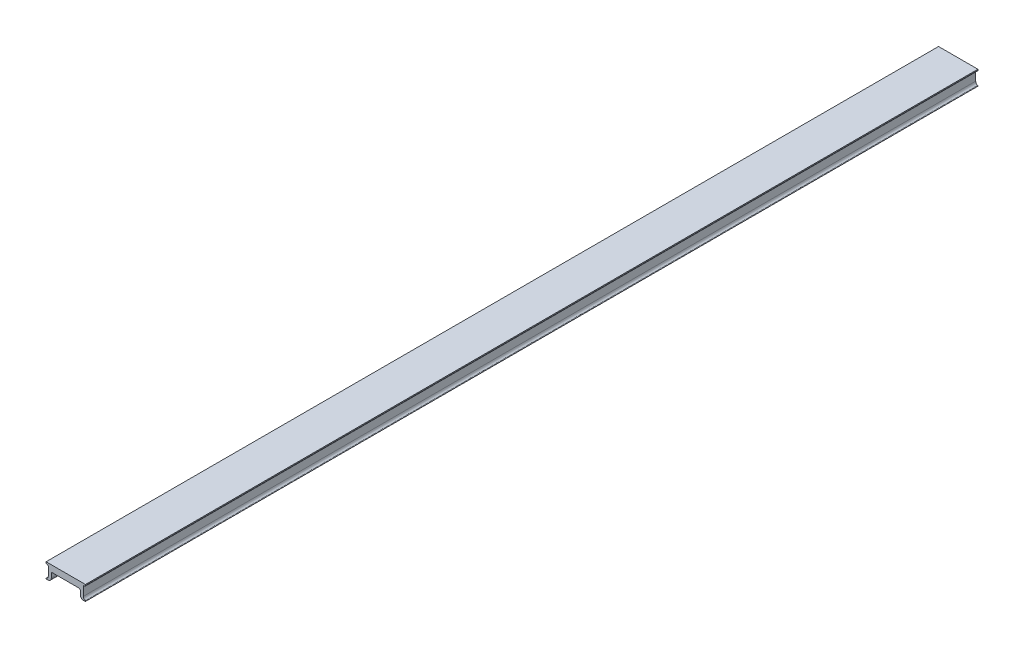
SolidWorks part; units mm, degrees
ref_plane "Płaszczyzna przednia" through (0, 0, 0) normal (0, 0, 1) x (1, 0, 0)
ref_plane "Płaszczyzna górna" through (0, 0, 0) normal (0, 1, 0) x (1, 0, 0)
ref_plane "Płaszczyzna prawa" through (0, 0, 0) normal (1, 0, 0) x (0, 0, -1)
sketch "Szkic1" plane through (0, 0, 0) normal (0, 0, 1) x (1, 0, 0)
  line L0 (92.01, 51.0774) -> (101.01, 51.0774)
  line L1 (96.51, 51.0774) -> (96.51, 47.86) construction
  line L2 (92.0832, 47.679) -> (92.4427, 47.679)
  line L3 (93.2003, 48.4365) -> (93.2003, 49.36)
  line L4 (93.4589, 49.6186) -> (99.5611, 49.6186)
  line L5 (101.01, 50.86) -> (101.01, 51.0774)
  line L6 (100.71, 50.66) -> (100.81, 50.66)
  line L7 (100.51, 48.46) -> (100.51, 50.46)
  line L8 (99.8197, 48.4365) -> (99.8197, 49.36)
  line L9 (100.9368, 47.679) -> (100.5773, 47.679)
  line L65 (92.51, 48.46) -> (92.51, 50.46)
  line L66 (92.31, 50.66) -> (92.21, 50.66)
  line L67 (92.01, 50.86) -> (92.01, 51.0774)
  arc A0 (92.0766, 47.86) -> (92.0832, 47.679) centre (92.0799, 47.7695) ccw
  arc A1 (92.4427, 47.679) -> (93.2003, 48.4365) centre (92.4427, 48.4365) ccw
  arc A2 (93.2003, 49.36) -> (93.4589, 49.6186) centre (93.4589, 49.36) cw
  arc A3 (101.01, 50.86) -> (100.81, 50.66) centre (100.81, 50.86) cw
  arc A4 (100.51, 50.46) -> (100.71, 50.66) centre (100.71, 50.46) cw
  arc A5 (100.9434, 47.86) -> (100.51, 48.46) centre (101.1095, 48.4365) cw
  arc A6 (99.8197, 49.36) -> (99.5611, 49.6186) centre (99.5611, 49.36) ccw
  arc A7 (100.5773, 47.679) -> (99.8197, 48.4365) centre (100.5773, 48.4365) cw
  arc A8 (100.9434, 47.86) -> (100.9368, 47.679) centre (100.9401, 47.7695) cw
  arc A47 (92.0766, 47.86) -> (92.51, 48.46) centre (91.9105, 48.4365) ccw
  arc A48 (92.51, 50.46) -> (92.31, 50.66) centre (92.31, 50.46) ccw
  arc A49 (92.01, 50.86) -> (92.21, 50.66) centre (92.21, 50.86) ccw
  point P29 (96.51, 49.6186)
  dimension "D1" = 0.0906
  dimension "D2" = 0.7576
  dimension "D3" = 0.2586
  dimension "D4" = 8
  dimension "D5" = 2
extrude "Boss-Extrude1" add sketch "Szkic1" along normal blind 204
